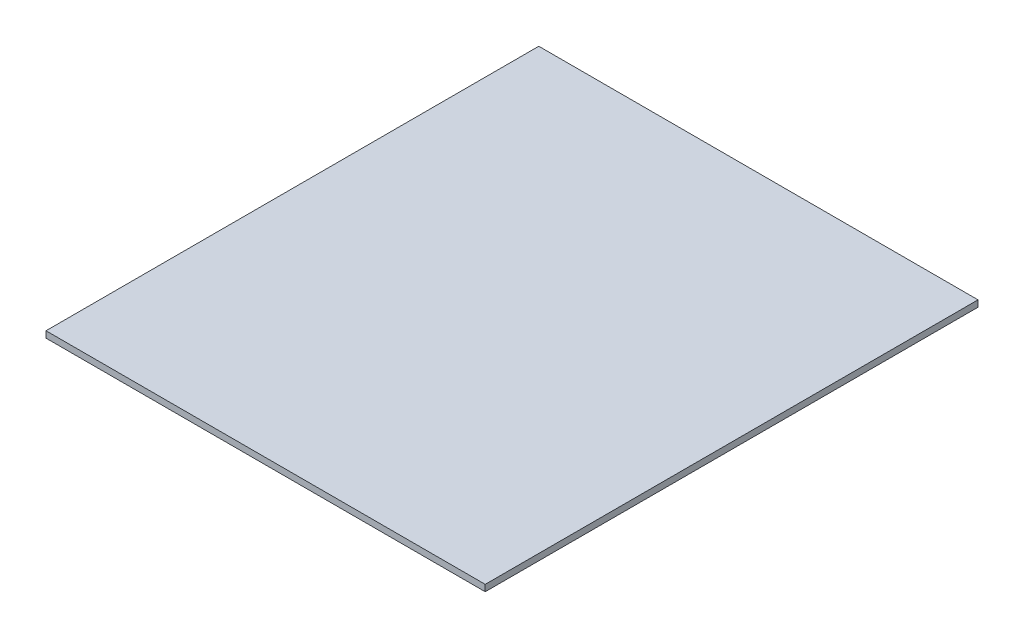
SolidWorks part; units mm, degrees
ref_plane "Front Plane" through (0, 0, 0) normal (0, 0, 1) x (1, 0, 0)
ref_plane "Top Plane" through (0, 0, 0) normal (0, 1, 0) x (1, 0, 0)
ref_plane "Right Plane" through (0, 0, 0) normal (1, 0, 0) x (0, 0, -1)
sketch "Sketch1" plane through (0, 0, 0) normal (0, 1, 0) x (1, 0, 0)
  line L1 (-205, -230) -> (205, -230)
  line L2 (-205, -230) -> (-205, 230)
  line L3 (-205, 230) -> (205, 230)
  line L4 (205, -230) -> (205, 230)
extrude "Boss-Extrude1" add sketch "Sketch1" along normal blind 6
